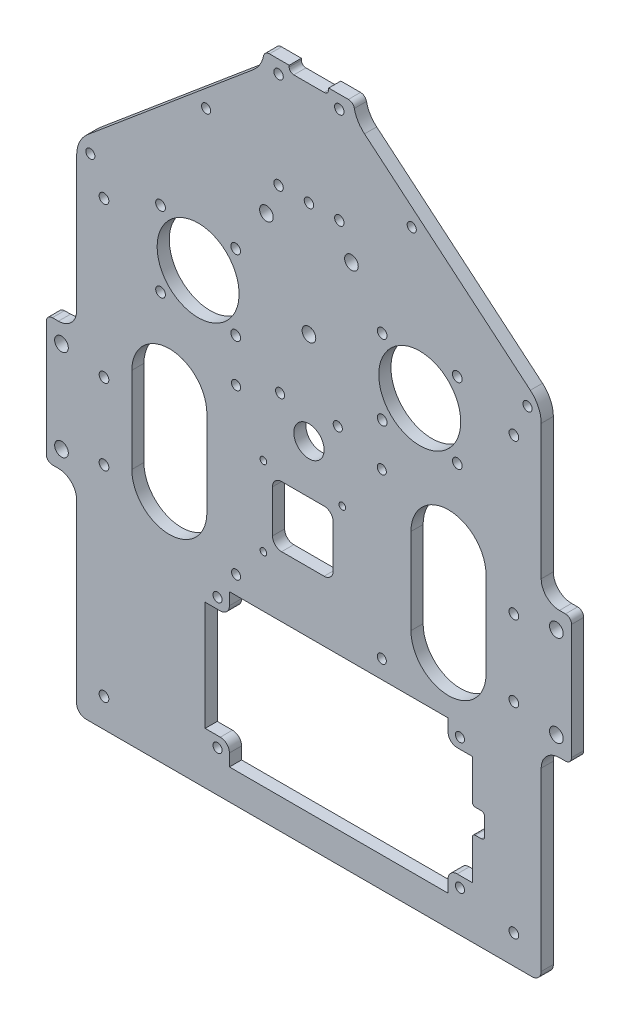
SolidWorks part; units mm, degrees
material "Thornel Mat VMA"
ref_plane "前视基准面" through (0, 0, 0) normal (0, 0, 1) x (1, 0, 0)
ref_plane "上视基准面" through (0, 0, 0) normal (0, 1, 0) x (1, 0, 0)
ref_plane "右视基准面" through (0, 0, 0) normal (1, 0, 0) x (0, 0, -1)
sketch "草图1" plane through (0, 0, 0) normal (0, 0, 1) x (1, 0, 0)
  line L0 (0, 0) -> (0, 27.5) construction
  line L1 (-14, 27.5) -> (14, 27.5) construction
  line L2 (-36.5, 0) -> (36.5, 0) construction
  line L3 (-20.1139, 33.2452) -> (-46.7609, 18.3225)
  line L4 (-24.4178, -17.1762) -> (-17.2603, -12.1414)
  line L5 (17.2603, -12.1414) -> (24.4178, -17.1762)
  line L6 (46.7609, 18.3225) -> (20.1139, 33.2452)
  line L7 (15, 41.9702) -> (15, 71.5)
  line L8 (13, 73.5) -> (-13, 73.5)
  line L9 (-15, 71.5) -> (-15, 41.9702)
  line L10 (0, 27.5) -> (0, 73.5) construction
  line L11 (24.1256, 12.3744) -> (36.5, 0) construction
  line L13 (10, 69.2) -> (-10, 69.2) construction
  line L14 (10, 69.2) -> (10, 37.5) construction
  line L15 (10, 37.5) -> (-10, 37.5) construction
  line L16 (-10, 69.2) -> (-10, 37.5) construction
  line L17 (10, 69.2) -> (-10, 37.5) construction
  line L18 (10, 37.5) -> (-10, 69.2) construction
  circle A0 centre (-14, 27.5) radius 2.25
  circle A1 centre (14, 27.5) radius 2.25
  circle A3 centre (36.5, 0) radius 13.5
  circle A6 centre (36.5, 0) radius 17.5 construction
  circle A7 centre (24.1256, 12.3744) radius 1.6
  circle A8 centre (48.8744, 12.3744) radius 1.6
  circle A9 centre (48.8744, -12.3744) radius 1.6
  circle A10 centre (24.1256, -12.3744) radius 1.6
  circle A11 centre (0, 0) radius 2.25
  circle A12 centre (-24.1256, -12.3744) radius 1.6
  circle A13 centre (-48.8744, -12.3744) radius 1.6
  circle A14 centre (-48.8744, 12.3744) radius 1.6
  circle A15 centre (-24.1256, 12.3744) radius 1.6
  circle A16 centre (-36.5, 0) radius 13.5
  arc A17 (24.4178, -17.1762) -> (46.7609, 18.3225) centre (36.5, 0) ccw
  arc A18 (-46.7609, 18.3225) -> (-24.4178, -17.1762) centre (-36.5, 0) ccw
  arc A19 (-17.2603, -12.1414) -> (17.2603, -12.1414) centre (0, -36.6787) cw
  arc A20 (20.1139, 33.2452) -> (15, 41.9702) centre (25, 41.9702) cw
  arc A21 (-20.1139, 33.2452) -> (-15, 41.9702) centre (-25, 41.9702) ccw
  arc A22 (-13, 73.5) -> (-15, 71.5) centre (-13, 71.5) ccw
  arc A23 (15, 71.5) -> (13, 73.5) centre (13, 71.5) ccw
  circle A24 centre (-10, 37.5) radius 1.55
  circle A25 centre (10, 37.5) radius 1.55
  circle A26 centre (-10, 69.2) radius 1.55
  circle A27 centre (10, 69.2) radius 1.55
  circle A28 centre (0, 37.5) radius 1.55
  point P22 (36.5, 0)
  point P42 (0, 53.35)
  point P51 (-15, 73.5)
  point P54 (15, 73.5)
  dimension "D3" = 4.5
  dimension "D5" = 27
  dimension "D6" = 35
  dimension "D8" = 3.2
  dimension "D9" = 21
  dimension "D10" = 30
  dimension "D15" = 10
  dimension "D16" = 2
  dimension "D20" = 3.1
  dimension "D1" = 27.5
  dimension "D2" = 28
  dimension "D4" = 73
  dimension "D11" = 45
  dimension "D12" = 46
  dimension "D13" = 30
  dimension "D14" = 8
  dimension "D17" = 31.7
  dimension "D18" = 20
  dimension "D19" = 10
  dimension "D7" = 4
extrude "凸台-拉伸1" add sketch "草图1" along normal blind 4
sketch "草图2" plane through (0, 0, 0) normal (0, 0, -1) x (-1, 0, 0)
  line L0 (0, -9.1) -> (0, 0) construction
  line L1 (-72.7, 3.4) -> (72.7, 3.4) construction
  line L2 (-72.7, 3.4) -> (-72.7, -21.6) construction
  line L3 (-72.7, -21.6) -> (72.7, -21.6) construction
  line L4 (72.7, 3.4) -> (72.7, -21.6) construction
  line L5 (-72.7, 3.4) -> (72.7, -21.6) construction
  line L6 (-72.7, -21.6) -> (72.7, 3.4) construction
  line L7 (34.0342, -20.8547) -> (72.2538, -25.3737)
  line L8 (76.5, -21.6) -> (76.5, 3.4)
  line L9 (74.1613, 6.9078) -> (46.7609, 18.3225)
  line L10 (-74.1613, 6.9078) -> (-46.7609, 18.3225)
  line L11 (-76.5, -21.6) -> (-76.5, 3.4)
  line L12 (-34.0342, -20.8547) -> (-72.2538, -25.3737)
  circle A0 centre (72.7, 3.4) radius 2.25
  circle A1 centre (72.7, -21.6) radius 2.25
  arc A4 (24.4178, -17.1762) -> (46.7609, 18.3225) centre (36.5, 0) ccw construction
  arc A5 (46.7609, 18.3225) -> (34.0342, -20.8547) centre (36.5, 0) cw
  arc A6 (76.5, 3.4) -> (74.1613, 6.9078) centre (72.7, 3.4) ccw
  arc A7 (72.2538, -25.3737) -> (76.5, -21.6) centre (72.7, -21.6) ccw
  circle A8 centre (-72.7, 3.4) radius 2.25
  circle A9 centre (-72.7, -21.6) radius 2.25
  arc A10 (-46.7609, 18.3225) -> (-34.0342, -20.8547) centre (-36.5, 0) ccw
  arc A11 (-76.5, 3.4) -> (-74.1613, 6.9078) centre (-72.7, 3.4) cw
  arc A12 (-72.2538, -25.3737) -> (-76.5, -21.6) centre (-72.7, -21.6) cw
  circle A13 centre (-72.7, 3.4) radius 2.1 construction
  point P0 (0, -9.1)
  dimension "D3" = 4.5
  dimension "D4" = 3.8
  dimension "D2" = 25
extrude "凸台-拉伸2" add sketch "草图2" against normal up to surface (4 mm away) up to face at (0, 28.5589, 4)
sketch "草图4" plane through (0, 0, 0) normal (0, 0, -1) x (-1, 0, 0)
  line L0 (-13, 73.5) -> (13, 73.5) construction
  line L1 (6.5, 73.5) -> (-6.5, 73.5)
  line L2 (6.5, 73.5) -> (6.5, 73)
  line L3 (5, 71.5) -> (-5, 71.5)
  line L4 (-6.5, 73.5) -> (-6.5, 73)
  line L5 (0, 64.35) -> (0, 71.5) construction
  arc A0 (6.5, 73) -> (5, 71.5) centre (5, 73) cw
  arc A1 (-5, 71.5) -> (-6.5, 73) centre (-5, 73) cw
  point P14 (-6.5, 71.5)
  dimension "D3" = 1.5
  dimension "D1" = 13
  dimension "D2" = 2
extrude "切除-拉伸2" cut sketch "草图4" against normal blind 10
sketch "草图5" plane through (0, 0, 0) normal (0, 0, -1) x (-1, 0, 0)
  line L0 (-72.7, 3.4) -> (-72.7, -21.6) construction
  line L1 (-72.7, -21.6) -> (72.7, -21.6) construction
  line L2 (72.7, -21.6) -> (72.7, 3.4) construction
  line L3 (72.7, 3.4) -> (-72.7, 3.4) construction
  line L4 (-72.7, -9.1) -> (72.7, -9.1) construction
  line L5 (0, 71.5) -> (0, -21.6) construction
  line L6 (-5, 71.5) -> (5, 71.5) construction
  line L7 (-23, 0) -> (-50, 0) construction
  line L8 (-36.5, 13.5) -> (-36.5, -13.5) construction
  circle A5 centre (-36.5, 0) radius 13.5 construction
sketch "草图6" plane through (0, 0, 0) normal (0, 0, 1) x (1, 0, 0)
  line L0 (-76.5, 3.4) -> (-76.5, -86.5)
  line L2 (-76.5, -86.5) -> (76.5, -86.5)
  line L3 (76.5, -86.5) -> (76.5, 3.4)
  line L4 (-76.5, 3.4) -> (-53.144, -23.1142)
  line L5 (-72.2538, -25.3737) -> (-34.0342, -20.8547) construction
  line L7 (34.0342, -20.8547) -> (72.2538, -25.3737) construction
  line L8 (53.144, -23.1142) -> (76.5, 3.4)
  line L9 (-53.144, -23.1142) -> (-20.839, -14.6588)
  line L10 (-24.4178, -17.1762) -> (-17.2603, -12.1414) construction
  line L11 (20.839, -14.6588) -> (53.144, -23.1142)
  line L12 (17.2603, -12.1414) -> (24.4178, -17.1762) construction
  line L13 (-20.839, -14.6588) -> (-2.25, 0)
  line L14 (-2.25, 0) -> (-2.25, -4.2711)
  line L15 (-2.25, -4.2711) -> (2.25, -4.2711)
  line L16 (2.25, -4.2711) -> (2.25, 0)
  line L17 (2.25, 0) -> (20.839, -14.6588)
  line L18 (-6.5, 73.5) -> (-13, 73.5) construction
  circle A0 centre (-72.7, -21.6) radius 2.25
  circle A1 centre (72.7, -21.6) radius 2.25
  circle A2 centre (0, 0) radius 2.25 construction
  dimension "D1" = 160
sketch "草图7" plane through (0, 0, 0) normal (0, 0, 1) x (1, 0, 0)
  circle A1 centre (-72.7, -21.6) radius 2.25
  circle A2 centre (72.7, 3.4) radius 2.3908
  circle A4 centre (72.7, -21.6) radius 2.25
  circle A5 centre (-72.7, 3.4) radius 2.25
extrude "凸台-拉伸3" add sketch "草图6" along normal blind 4
extrude "凸台-拉伸5" add sketch "草图7" along normal blind 4
ref_plane "基准面1" through (-15, 41.9702, 4) normal (0, -1, 0) x (-1, 0, 0)
sketch "草图10" plane through (0, 0, 4) normal (0, 0, 1) x (1, 0, 0)
  line L0 (0, 71.5) -> (0, -86.5) construction
  line L1 (5, 71.5) -> (-5, 71.5) construction
  line L2 (-76.5, -86.5) -> (76.5, -86.5) construction
  line L3 (-76.5, -58.5) -> (76.5, -58.5) construction
  line L4 (-76.5, 3.4) -> (-76.5, -86.5) construction
  line L5 (76.5, -86.5) -> (76.5, 3.4) construction
  line L6 (-6.5, 73.5) -> (-13, 73.5) construction
  circle A0 centre (67.5, -46) radius 1.6
  circle A1 centre (67.5, -71) radius 1.6
  circle A2 centre (-67.5, -71) radius 1.6
  circle A3 centre (-67.5, -46) radius 1.6
  dimension "D1" = 3.2
  dimension "D2" = 25
  dimension "D3" = 135
  dimension "D4" = 132
extrude "切除-拉伸3" cut sketch "草图10" against normal blind 6
sketch "草图11" plane through (0, 0, 0) normal (0, 0, 1) x (1, 0, 0)
  line L0 (-76.5, -86.5) -> (-76.5, -146.5)
  line L1 (-76.5, -146.5) -> (76.5, -146.5)
  line L2 (76.5, -146.5) -> (76.5, -86.5)
  line L3 (76.5, -86.5) -> (-76.5, -86.5)
  dimension "D1" = 60
extrude "凸台-拉伸6" add sketch "草图11" along normal blind 4
sketch "草图12" plane through (0, 0, 4) normal (0, 0, 1) x (1, 0, 0)
  line L0 (0, 80.328) -> (0, -147.1605) construction
  line L1 (-6.5, 73.5) -> (-13, 73.5) construction
  line L2 (-24, -26.5) -> (24, -26.5) construction
  line L3 (-24, -26.5) -> (-24, -80.5) construction
  line L4 (-24, -80.5) -> (24, -80.5) construction
  line L5 (24, -26.5) -> (24, -80.5) construction
  line L6 (0, -80.5) -> (0, -26.5) construction
  line L7 (-24, -53.5) -> (24, -53.5) construction
  circle A0 centre (24, -26.5) radius 1.5
  circle A1 centre (-24, -26.5) radius 1.5
  circle A2 centre (24, -80.5) radius 1.5
  circle A3 centre (-24, -80.5) radius 1.5
  point P3 (0, -53.5)
  dimension "D3" = 3
  dimension "D1" = 48
  dimension "D2" = 54
  dimension "D4" = 127
extrude "切除-拉伸4" cut sketch "草图12" against normal blind 10
sketch "草图14" plane through (0, 0, 4) normal (0, 0, 1) x (1, 0, 0)
  line L0 (-76.5, -37.5) -> (-86.5, -37.5)
  line L1 (-76.5, 3.4) -> (-76.5, -146.5) construction
  line L2 (-86.5, -37.5) -> (-86.5, -79.5)
  line L3 (-86.5, -79.5) -> (-76.5, -79.5)
  line L4 (-76.5, -37.5) -> (-76.5, -79.5)
  line L5 (-67.5, -46) -> (-67.5, -71) construction
  line L6 (-67.5, -58.5) -> (-94.7078, -58.5) construction
  line L7 (-81.5, -37.5) -> (-81.5, -79.5) construction
  line L10 (0, 71.5) -> (0, -146.5) construction
  line L11 (5, 71.5) -> (-5, 71.5) construction
  line L12 (-76.5, -146.5) -> (76.5, -146.5) construction
  line L15 (81.5, -37.5) -> (81.5, -79.5) construction
  line L16 (67.5, -58.5) -> (94.7078, -58.5) construction
  line L18 (76.5, -37.5) -> (76.5, -79.5)
  line L19 (86.5, -79.5) -> (76.5, -79.5)
  line L20 (86.5, -37.5) -> (86.5, -79.5)
  line L21 (76.5, -37.5) -> (86.5, -37.5)
  circle A0 centre (-81.5, -43.5) radius 2.25
  circle A1 centre (-81.5, -73.5) radius 2.25
  circle A2 centre (81.5, -73.5) radius 2.25
  circle A3 centre (81.5, -43.5) radius 2.25
  dimension "D1" = 4.5
  dimension "D2" = 4.5
  dimension "D4" = 15
  dimension "D5" = 15
  dimension "D3" = 10
  dimension "D6" = 42
extrude "凸台-拉伸7" add sketch "草图14" against normal blind 4
fillet "圆角1" radius 6 4 edges at (76.5, -79.5, 2) (76.5, -37.5, 2) (-76.5, -79.5, 2) (-76.5, -37.5, 2)
sketch "草图15" plane through (0, 0, 4) normal (0, 0, 1) x (1, 0, 0)
  line L0 (0, 71.5) -> (0, -146.5) construction
  line L1 (5, 71.5) -> (-5, 71.5) construction
  line L2 (-76.5, -146.5) -> (76.5, -146.5) construction
  line L3 (-15, -43.5) -> (-15, -69.5) construction
  line L4 (-15, -56.5) -> (11, -56.5) construction
  line L5 (-15, -43.5) -> (11, -43.5) construction
  line L6 (11, -43.5) -> (11, -69.5) construction
  line L7 (11, -69.5) -> (-15, -69.5) construction
  line L8 (-2, -43.5) -> (-2, -69.5) construction
  line L9 (-86.5, -58.5) -> (86.5, -58.5) construction
  line L10 (-86.5, -37.5) -> (-86.5, -79.5) construction
  line L11 (86.5, -79.5) -> (86.5, -37.5) construction
  circle A0 centre (-15, -43.5) radius 1.1
  circle A1 centre (11, -43.5) radius 1.1
  circle A2 centre (-15, -69.5) radius 1.1
  dimension "D1" = 2.2
  dimension "D2" = 2.2
  dimension "D3" = 15
  dimension "D4" = 11
  dimension "D5" = 2.2
  dimension "D6" = 26
  dimension "D7" = 2
extrude "切除-拉伸6" cut sketch "草图15" against normal blind 4
sketch "草图17" plane through (0, 0, 4) normal (0, 0, 1) x (1, 0, 0)
  line L0 (-52.6649, 37.5) -> (-76.5, 37.5) construction
  line L1 (-76.5, 2.8509) -> (-76.5, 17.5)
  line L2 (-76.5, 3.4) -> (-76.5, -31.5) construction
  line L3 (-76.5, 37.5) -> (-94.7832, 37.5) construction
  line L4 (-76.5, 17.5) -> (-15, 69.1046)
  line L6 (0, 37.5) -> (-52.6649, 37.5) construction
  line L7 (-15, 69.1046) -> (-15, 31.9368)
  line L8 (-15, 31.9368) -> (-76.5, 2.8509)
  line L9 (-76.5, -14.05) -> (-76.5, 2.8509) construction
  line L10 (-76.5, 17.5) -> (-76.5, 37.5) construction
  line L11 (0, 71.5) -> (0, -146.5) construction
  line L12 (5, 71.5) -> (-5, 71.5) construction
  line L13 (-76.5, -146.5) -> (76.5, -146.5) construction
  line L14 (76.5, 17.5) -> (76.5, 37.5) construction
  line L15 (76.5, 37.5) -> (94.7832, 37.5) construction
  line L16 (52.6649, 37.5) -> (76.5, 37.5) construction
  line L17 (15, 31.9368) -> (76.5, 2.8509)
  line L18 (15, 69.1046) -> (15, 31.9368)
  line L19 (76.5, 17.5) -> (15, 69.1046)
  line L20 (76.5, 2.8509) -> (76.5, 17.5)
  line L21 (-6.5, 73.5) -> (-13, 73.5) construction
  dimension "D1" = 68.0312
  dimension "D2" = 56
  dimension "D3" = 40
extrude "凸台-拉伸9" add sketch "草图17" against normal blind 4
fillet "圆角8" radius 2 4 edges at (86.5, -79.5, 2) (86.5, -37.5, 2) (-86.5, -37.5, 2) (-86.5, -79.5, 2)
sketch "草图18" plane through (0, 0, 4) normal (0, 0, 1) x (1, 0, 0)
  line L3 (-6.5, 73.5) -> (-13, 73.5) construction
  line L4 (-34.1808, -86.5) -> (53.8192, -86.5)
  line L5 (-34.1808, -86.5) -> (-34.1808, -136.5)
  line L6 (-34.1808, -136.5) -> (53.8192, -136.5)
  line L7 (53.8192, -86.5) -> (53.8192, -136.5)
  line L8 (9.8192, -136.5) -> (9.8192, -86.5) construction
  line L9 (-34.1808, -111.5) -> (53.8192, -111.5) construction
  point P6 (9.8192, -111.5)
  dimension "D1" = 88
  dimension "D2" = 50
  dimension "D3" = 185
extrude "切除-拉伸7" cut sketch "草图18" against normal blind 10
sketch "草图19" plane through (0, 0, 4) normal (0, 0, 1) x (1, 0, 0)
  line L0 (9.8192, -86.5) -> (9.8192, -136.5) construction
  line L1 (53.8192, -86.5) -> (-34.1808, -86.5) construction
  line L2 (-34.1808, -136.5) -> (53.8192, -136.5) construction
  line L3 (-34.1808, -111.5) -> (53.8192, -111.5) construction
  line L4 (-34.1808, -86.5) -> (-34.1808, -136.5) construction
  line L5 (53.8192, -136.5) -> (53.8192, -86.5) construction
  line L6 (45.8192, -86.5) -> (45.8192, -93.5)
  line L7 (-34.1808, -86.5) -> (-26.1808, -86.5)
  line L8 (-34.1808, -86.5) -> (-34.1808, -93.5)
  line L9 (-34.1808, -93.5) -> (-26.1808, -93.5)
  line L10 (-26.1808, -86.5) -> (-26.1808, -93.5)
  line L11 (53.8192, -93.5) -> (45.8192, -93.5)
  line L12 (53.8192, -86.5) -> (53.8192, -93.5)
  line L13 (53.8192, -86.5) -> (45.8192, -86.5)
  line L14 (53.8192, -136.5) -> (45.8192, -136.5)
  line L15 (53.8192, -136.5) -> (53.8192, -129.5)
  line L16 (53.8192, -129.5) -> (45.8192, -129.5)
  line L17 (-26.1808, -136.5) -> (-26.1808, -129.5)
  line L18 (-34.1808, -129.5) -> (-26.1808, -129.5)
  line L19 (-34.1808, -136.5) -> (-34.1808, -129.5)
  line L20 (-34.1808, -136.5) -> (-26.1808, -136.5)
  line L21 (45.8192, -136.5) -> (45.8192, -129.5)
  dimension "D1" = 7
  dimension "D2" = 8
extrude "凸台-拉伸10" add sketch "草图19" against normal blind 4
fillet "圆角9" radius 3 4 edges at (45.8192, -129.5, 2) (-26.1808, -129.5, 2) (45.8192, -93.5, 2) (-26.1808, -93.5, 2)
sketch "草图20" plane through (0, 0, 4) normal (0, 0, 1) x (1, 0, 0)
  line L0 (9.8192, -86.5) -> (9.8192, -136.5) construction
  line L1 (45.8192, -86.5) -> (-26.1808, -86.5) construction
  line L2 (-26.1808, -136.5) -> (45.8192, -136.5) construction
  line L3 (-34.1808, -111.5) -> (53.8192, -111.5) construction
  line L4 (-34.1808, -93.5) -> (-34.1808, -129.5) construction
  line L5 (53.8192, -129.5) -> (53.8192, -93.5) construction
  circle A0 centre (49.7442, -90.025) radius 1.5
  circle A1 centre (-30.1058, -90.025) radius 1.5
  circle A2 centre (49.7442, -132.975) radius 1.5
  circle A3 centre (-30.1058, -132.975) radius 1.5
  dimension "D1" = 79.85
  dimension "D2" = 42.95
  dimension "D3" = 3
extrude "切除-拉伸8" cut sketch "草图20" against normal blind 4
fillet "圆角10" radius 3 2 edges at (76.5, -146.5, 2) (-76.5, -146.5, 2)
sketch "草图21" plane through (0, 0, 0) normal (0, 0, 1) x (1, 0, 0)
  line L1 (53.8192, -129.5) -> (53.8192, -93.5) construction
  line L2 (49.8192, -107.5) -> (57.8192, -107.5)
  line L3 (49.8192, -107.5) -> (49.8192, -115.5)
  line L4 (49.8192, -115.5) -> (57.8192, -115.5)
  line L5 (57.8192, -107.5) -> (57.8192, -115.5)
  line L6 (53.8192, -115.5) -> (53.8192, -107.5) construction
  line L7 (49.8192, -111.5) -> (57.8192, -111.5) construction
  point P0 (53.8192, -111.5)
  dimension "D1" = 8
  dimension "D2" = 4
extrude "切除-拉伸10" cut sketch "草图21" along normal blind 4
fillet "圆角12" radius 1 4 edges at (53.8192, -115.5, 2) (57.8192, -115.5, 2) (57.8192, -107.5, 2) (53.8192, -107.5, 2)
sketch "草图22" plane through (0, 0, 4) normal (0, 0, 1) x (1, 0, 0)
  line L0 (0, 71.5) -> (0, -146.5) construction
  line L1 (5, 71.5) -> (-5, 71.5) construction
  line L2 (-73.5, -146.5) -> (73.5, -146.5) construction
  line L3 (45.9713, -39.4347) -> (45.9713, -67.7176) construction
  line L4 (58.332, -39.4347) -> (58.332, -67.7176)
  line L5 (33.6106, -39.4347) -> (33.6106, -67.7176)
  line L6 (-45.9713, -39.4347) -> (-45.9713, -67.7176) construction
  line L7 (-58.332, -39.4347) -> (-58.332, -67.7176)
  line L8 (-33.6106, -39.4347) -> (-33.6106, -67.7176)
  arc A0 (58.332, -39.4347) -> (33.6106, -39.4347) centre (45.9713, -39.4347) ccw
  arc A1 (33.6106, -67.7176) -> (58.332, -67.7176) centre (45.9713, -67.7176) ccw
  arc A2 (-58.332, -39.4347) -> (-33.6106, -39.4347) centre (-45.9713, -39.4347) cw
  arc A3 (-33.6106, -67.7176) -> (-58.332, -67.7176) centre (-45.9713, -67.7176) cw
  point P8 (45.9713, -53.5762)
  point P17 (-45.9713, -53.5762)
extrude "切除-拉伸11" cut sketch "草图22" against normal blind 4
sketch "草图23" plane through (0, 0, 0) normal (0, 0, -1) x (-1, 0, 0)
  line L0 (0, 71.5) -> (0, -146.5) construction
  line L1 (-5, 71.5) -> (5, 71.5) construction
  line L2 (73.5, -146.5) -> (-73.5, -146.5) construction
  line L3 (14, 27.5) -> (-14, 27.5) construction
  line L4 (-9.5, -21.5) -> (9.5, -21.5) construction
  circle A0 centre (-9.5, -21.5) radius 1.5
  circle A1 centre (9.5, -21.5) radius 1.5
  dimension "D1" = 19
  dimension "D2" = 3
  dimension "D3" = 49
extrude "切除-拉伸12" cut sketch "草图23" against normal blind 10
sketch "草图24" plane through (0, 0, 4) normal (0, 0, 1) x (1, 0, 0)
  line L0 (0, 76.9644) -> (0, -177.2162) construction
  line L1 (-76.5, 17.5) -> (76.5, 17.5) construction
  circle A0 centre (-72, 15.5) radius 1.5
  circle A1 centre (72, 15.5) radius 1.5
  dimension "D1" = 3
  dimension "D2" = 4
  dimension "D3" = 72
extrude "切除-拉伸13" cut sketch "草图24" against normal blind 10
sketch "草图25" plane through (0, 0, 4) normal (0, 0, 1) x (1, 0, 0)
  line L0 (-72, 15.5) -> (-33.8639, 47.5) construction
  line L1 (-15, 69.1046) -> (-76.5, 17.5) construction
  line L2 (0, 78.5145) -> (0, -180.1408) construction
  circle A0 centre (-33.8639, 47.5) radius 1.5
  circle A1 centre (-72, 15.5) radius 1.5 construction
  circle A2 centre (33.8639, 47.5) radius 1.5
  dimension "D1" = 3
  dimension "D2" = 32
extrude "切除-拉伸14" cut sketch "草图25" against normal blind 10
sketch "草图27" plane through (0, 0, 4) normal (0, 0, 1) x (1, 0, 0)
  line L0 (0, 79.381) -> (0, -152.688) construction
  line L1 (-86.5, -58.5) -> (86.5, -58.5) construction
  line L2 (-86.5, -39.5) -> (-86.5, -77.5) construction
  line L3 (86.5, -77.5) -> (86.5, -39.5) construction
  circle A0 centre (0, -30.5) radius 5
  dimension "D1" = 10
  dimension "D2" = 28
extrude "切除-拉伸15" cut sketch "草图27" against normal blind 10
sketch "草图28" plane through (0, 0, 4) normal (0, 0, 1) x (1, 0, 0)
  line L0 (-15, -43.5) -> (-15, -69.5) construction
  line L1 (-15, -69.5) -> (11, -43.5) construction
  line L2 (11, -43.5) -> (-15, -43.5) construction
  line L4 (5, -66.5) -> (-9, -66.5)
  line L5 (8, -63.5) -> (8, -49.5)
  line L6 (5, -46.5) -> (-9, -46.5)
  line L7 (-12, -63.5) -> (-12, -49.5)
  line L8 (-2, -46.5) -> (-2, -66.5) construction
  line L9 (8, -56.5) -> (-12, -56.5) construction
  arc A0 (-9, -66.5) -> (-12, -63.5) centre (-9, -63.5) cw
  arc A1 (-9, -46.5) -> (-12, -49.5) centre (-9, -49.5) ccw
  arc A2 (8, -49.5) -> (5, -46.5) centre (5, -49.5) ccw
  arc A3 (5, -66.5) -> (8, -63.5) centre (5, -63.5) ccw
  point P6 (-2, -56.5)
  point P15 (-12, -46.5)
  point P18 (8, -46.5)
  dimension "D2" = 3
  dimension "D1" = 20
extrude "切除-拉伸16" cut sketch "草图28" against normal blind 10
fillet "圆角5" radius 10 2 edges at (-76.5, 17.5, 2) (76.5, 17.5, 2)
fillet "圆角6" radius 10 2 edges at (-15, 69.1046, 2) (15, 69.1046, 2)
sketch "草图31" plane through (0, 0, 4) normal (0, 0, 1) x (1, 0, 0)
  line L0 (-67.5, 13.1693) -> (-67.5, -152.3951) construction
  line L1 (0, 75.6519) -> (0, -213.1845) construction
  circle A0 centre (-67.5, 5) radius 1.6
  circle A1 centre (-67.5, -46) radius 1.6 construction
  circle A2 centre (-67.5, -137) radius 1.6
  circle A3 centre (-67.5, -71) radius 1.6 construction
  circle A4 centre (67.5, 5) radius 1.6
  circle A5 centre (67.5, -137) radius 1.6
  dimension "D1" = 3.2
  dimension "D2" = 51
  dimension "D3" = 3.2
  dimension "D4" = 66
extrude "切除-拉伸17" cut sketch "草图31" against normal blind 10
